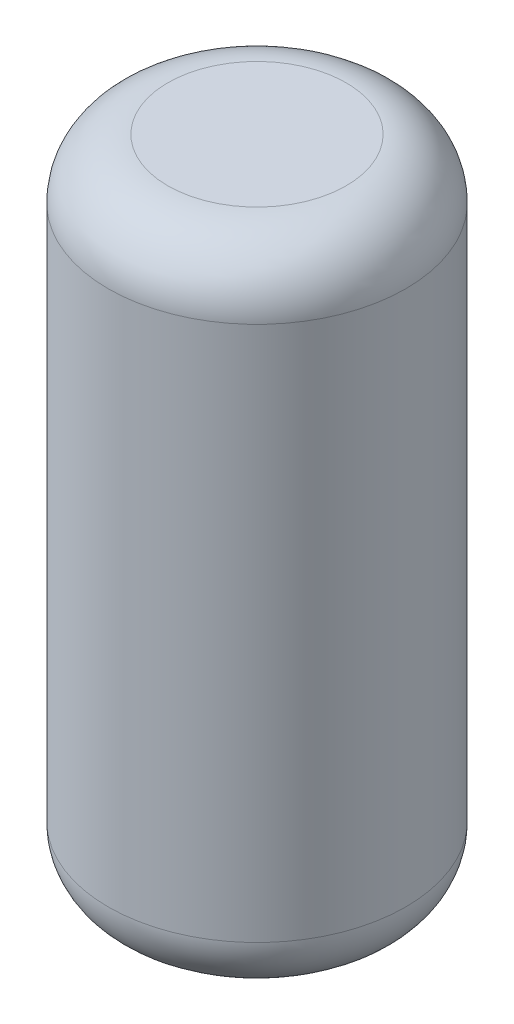
SolidWorks part; units mm, degrees
ref_plane "Front Plane" through (0, 0, 0) normal (0, 0, 1) x (1, 0, 0)
ref_plane "Top Plane" through (0, 0, 0) normal (0, 1, 0) x (1, 0, 0)
ref_plane "Right Plane" through (0, 0, 0) normal (1, 0, 0) x (0, 0, -1)
sketch "Sketch1" plane through (0, 0, 0) normal (0, 1, 0) x (1, 0, 0)
  circle A0 centre (0, 0) radius 2.5
  dimension "D1" = 5
extrude "Boss-Extrude1" add sketch "Sketch1" along normal blind 11
fillet "Fillet2" radius 1 2 edges at (0, 0, 2.5) (0, 11, 2.5)
